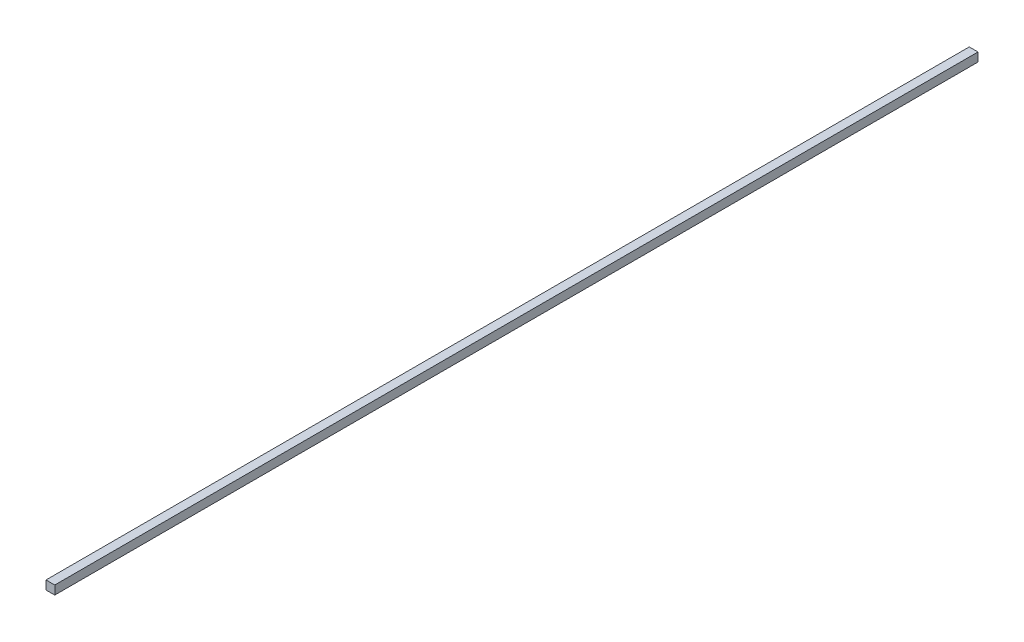
SolidWorks part; units mm, degrees
ref_plane "Front Plane" through (0, 0, 0) normal (0, 0, 1) x (1, 0, 0)
ref_plane "Top Plane" through (0, 0, 0) normal (0, 1, 0) x (1, 0, 0)
ref_plane "Right Plane" through (0, 0, 0) normal (1, 0, 0) x (0, 0, -1)
sketch "Sketch1" plane through (0, 0, 0) normal (0, 0, 1) x (1, 0, 0)
  line L4 (0, -43.6391) -> (0, -41.6391)
  line L5 (0, -41.6391) -> (-2, -41.6391)
  line L6 (-2, -41.6391) -> (-2, -43.6391)
  line L7 (-2, -43.6391) -> (0, -43.6391)
  line L8 (0, -43.6391) -> (0, -41.6391)
  line L10 (-2, -41.6391) -> (-2, -43.6391)
  line L11 (-2, -43.6391) -> (0, -43.6391)
  line L26 (0, -41.6391) -> (-2, -41.6391)
  dimension "D1" = 0
extrude "Boss-Extrude1" add sketch "Sketch1" along normal blind 211
sketch "Sketch2" plane through (0, 0, 211) normal (0, 0, 1) x (1, 0, 0)
  line L0 (-2, -43.6391) -> (0, -41.6391)
  line L1 (0, -41.6391) -> (-2, -41.6391)
  line L2 (-2, -41.6391) -> (0, -43.6391)
  circle A0 centre (-1, -42.6391) radius 2.7827
  point P8 (-1, -42.6391)
